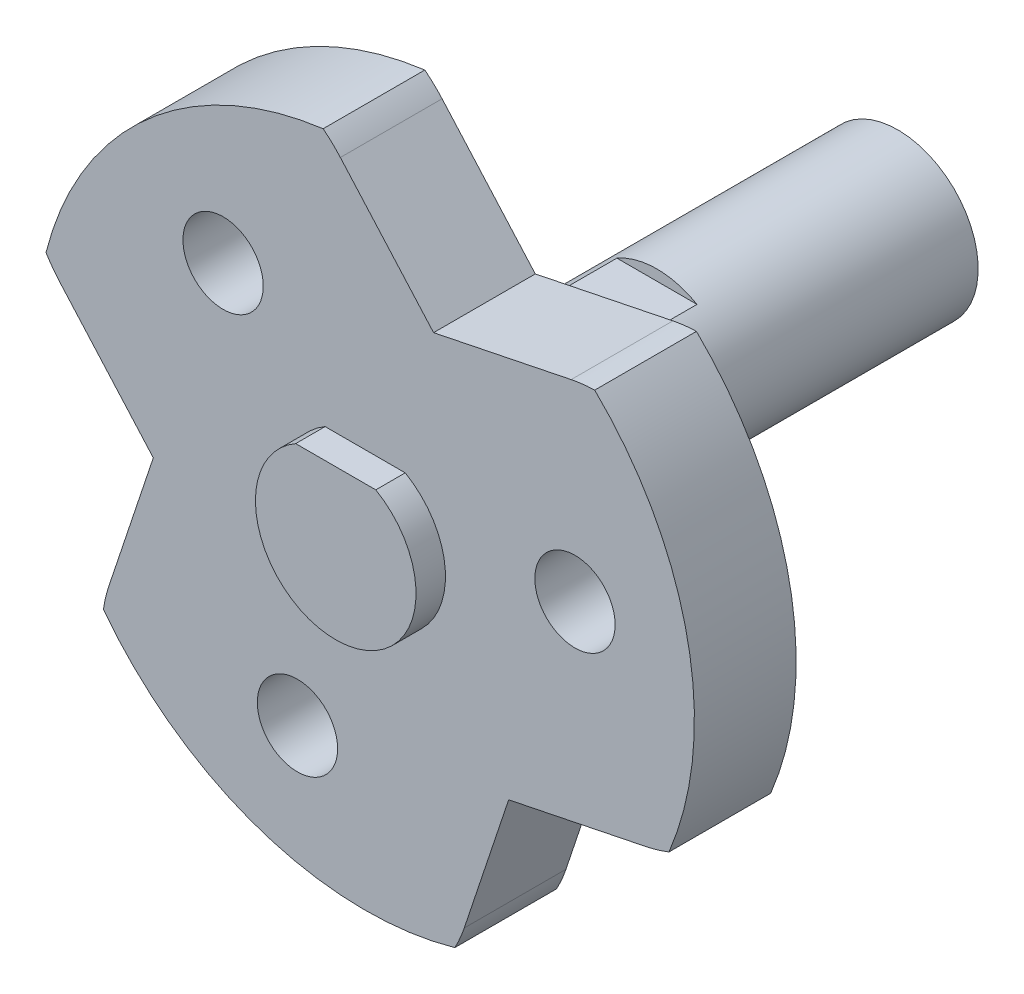
SolidWorks part; units mm, degrees
other "eje"
other "acople_prueba"
ref_plane "Alzado" through (0, 0, 0) normal (0, 0, 1) x (1, 0, 0)
ref_plane "Planta" through (0, 0, 0) normal (0, 1, 0) x (1, 0, 0)
ref_plane "Vista lateral" through (0, 0, 0) normal (1, 0, 0) x (0, 0, -1)
sketch "Croquis1" plane through (0, 0, 0) normal (0, 0, 1) x (1, 0, 0)
  line L0 (-3.993, 3) -> (5.9222, 3) construction
  line L1 (-1.4967, 2.6) -> (1.4967, 2.6)
  line L2 (-4.4025, -3) -> (5.8838, -3) construction
  arc A0 (-1.4967, 2.6) -> (1.4967, 2.6) centre (0, 0) ccw
  dimension "D1" = 6
  dimension "D2" = 5.6
extrude "Saliente-Extruir1" add sketch "Croquis1" along normal blind 12 contours A0 L1
sketch "Croquis2" plane through (0, 0, 0) normal (0, 0, -1) x (-1, 0, 0)
  circle A0 centre (0, 0) radius 3
extrude "Saliente-Extruir2" add sketch "Croquis2" along normal blind 9
sketch "Croquis3" plane through (0, 0, 12) normal (0, 0, 1) x (1, 0, 0)
  line L0 (-1.5492, 2.8) -> (1.5492, 2.8)
  line L1 (-1.4967, 2.6) -> (1.4967, 2.6) construction
  line L2 (-1.4967, 2.6) -> (1.4967, 2.6) construction
  line L4 (-4.4025, -3) -> (5.8838, -3) construction
  line L6 (-1.4967, 2.6) -> (1.4967, 2.6) construction
  arc A0 (-1.5492, 2.8) -> (1.5492, 2.8) centre (0, 0) ccw
  arc A1 (-1.4967, 2.6) -> (1.4967, 2.6) centre (0, 0) ccw construction
  circle A2 centre (0, 0) radius 5.7
  dimension "D1" = 0.2
  dimension "D3" = 2.5
  dimension "D2" = 0.2
  dimension "D4" = 5.6
extrude "Saliente-Extruir3" add sketch "Croquis3" against normal blind 8 separate body
sketch "Croquis4" plane through (0, 0, 4) normal (0, 0, -1) x (-1, 0, 0)
  circle A0 centre (0, 0) radius 3.2
  circle A1 centre (0, 0) radius 8.2
  arc A2 (-1.5492, 2.8) -> (1.5492, 2.8) centre (0, 0) ccw construction
extrude "Saliente-Extruir4" add sketch "Croquis4" along normal blind 5
sketch "Croquis5" plane through (0, 0, 4) normal (0, 0, 1) x (1, 0, 0)
  circle A0 centre (0, 0) radius 4.75
  circle A1 centre (0, 0) radius 8.2
  dimension "D1" = 9.5
extrude "Cortar-Extruir1" cut sketch "Croquis5" against normal through all and the other way through all
sketch "Croquis6" plane through (0, 0, -1) normal (0, 0, -1) x (-1, 0, 0)
  circle A0 centre (0, 0) radius 14.5
  circle A1 centre (0, 0) radius 4.75
  dimension "D1" = 29
extrude "Saliente-Extruir5" add sketch "Croquis6" against normal through all
sketch "Croquis7" plane through (0, 0, -1) normal (0, 0, -1) x (-1, 0, 0)
  circle A0 centre (0, 0) radius 8 construction
  circle A3 centre (-7.8376, 1.6038) radius 2.4
  circle A11 centre (5.3078, 5.9856) radius 2.4
  circle A12 centre (2.5298, -7.5895) radius 2.4
  point P11 (0, 0)
  point P17 (0, 0)
  dimension "D1" = 16
  dimension "D2" = 3
extrude "Cortar-Extruir2" cut sketch "Croquis7" against normal through all
sketch "Croquis8" plane through (0, 0, 12) normal (0, 0, 1) x (1, 0, 0)
  line L0 (-1.5492, 2.8) -> (1.5492, 2.8)
  line L1 (1.5492, 2.8) -> (1.806, 2.5219)
  circle A1 centre (-2.5298, -7.5895) radius 2.4
  circle A2 centre (0, 0) radius 8 construction
  circle A3 centre (0.0015, 0.0009) radius 8 construction
  circle A5 centre (0.0015, -0.0009) radius 8 construction
  circle A10 centre (7.8391, 1.603) radius 2.4 construction
  circle A11 centre (-5.3063, 5.9865) radius 2.4 construction
  circle A12 centre (-5.3078, 5.9856) radius 2.4
  circle A13 centre (7.8376, 1.6038) radius 2.4
  circle A14 centre (0.0015, 0.0009) radius 14.5017
  point P17 (0.001, 0)
  dimension "D1" = 3
extrude "Saliente-Extruir6" add sketch "Croquis8" along normal blind 3.8
sketch "Croquis9" plane through (0, 0, -1) normal (0, 0, -1) x (-1, 0, 0)
  circle A0 centre (0, 0) radius 14.5
extrude "Cortar-Extruir3" cut sketch "Croquis9" against normal blind 2.5
sketch "Croquis10" plane through (0, 0, 1.5) normal (0, 0, -1) x (-1, 0, 0)
  circle A0 centre (0, 0) radius 14.5
extrude "Cortar-Extruir4" cut sketch "Croquis10" against normal blind 5.6
sketch "Croquis11" plane through (0, 0, 15.8) normal (0, 0, 1) x (1, 0, 0)
  line L0 (-2.5298, -7.5895) -> (0, 0) construction
  line L1 (0, 0) -> (7.8376, 1.6038) construction
  line L2 (0, 0) -> (-5.3078, 5.9856) construction
  line L3 (0, 0) -> (9.6203, -10.8489) construction
  line L4 (0, 0) -> (4.5853, 13.7559) construction
  line L5 (0, 0) -> (-14.2056, -2.907) construction
  circle A0 centre (0, 0) radius 14.5 construction
  dimension "D1" = 120
  dimension "D2" = 60
  dimension "D3" = 60
  dimension "D4" = 60
sketch "Croquis12" plane through (0, 0, 15.8) normal (0, 0, 1) x (1, 0, 0)
  line L0 (0, 0) -> (-4.5853, -13.7559) construction
  line L1 (0, 0) -> (-9.6203, 10.8489) construction
  line L2 (0, 0) -> (14.2056, 2.907) construction
  line L3 (2.6219, -14.261) -> (5.3605, -6.0451)
  line L4 (5.3605, -6.0451) -> (13.845, -4.3089)
  line L5 (0, 0) -> (9.6203, -10.8489) construction
  line L6 (2.6219, -14.261) -> (13.845, -4.3089) construction
  line L7 (-13.6613, 4.8598) -> (-7.9155, -1.6198)
  line L8 (-7.9155, -1.6198) -> (-10.6541, -9.8356)
  line L9 (11.0394, 9.4011) -> (2.555, 7.6649)
  line L10 (2.555, 7.6649) -> (-3.1908, 14.1446)
  circle A0 centre (0, 0) radius 14.5
  circle A1 centre (0, 0) radius 14.5 construction
  circle A2 centre (-2.5298, -7.5895) radius 2.4 construction
  circle A3 centre (-5.3078, 5.9856) radius 2.4 construction
  circle A4 centre (7.8376, 1.6038) radius 2.4 construction
  circle A5 centre (0, 0) radius 14.5
  circle A6 centre (0, 0) radius 14.5
  point P32 (0, 0)
  circle M12 centre (0, 0) radius 14.5
  dimension "D1" = 120
  dimension "D2" = 120
  dimension "D3" = 120
  dimension "D4" = 60
  dimension "D5" = 120
  dimension "D6" = 15
  dimension "D7" = 3
extrude "Cortar-Extruir5" cut sketch "Croquis12" against normal up to next (8.7 mm away) contours L8 L7 M12 | L10 L9 M12 | L4 L3 M12
fillet "Redondeo2" radius 5 6 edges at (-13.6613, 4.8598, 11.45) (-3.1908, 14.1446, 11.45) (11.0394, 9.4011, 11.45) (13.845, -4.3089, 11.45) (2.6219, -14.261, 11.45) (-10.6541, -9.8356, 11.45)
ref_plane "Plano1" through (0, 0, 10.9) normal (0, 0, -1) x (-1, 0, 0)
sketch "Croquis13" plane through (0, 0, 15.8) normal (0, 0, 1) x (1, 0, 0)
  line L12 (-12.1456, 1.6433) -> (-9.0468, -1.8513)
  line L13 (-9.0468, -1.8513) -> (-10.5237, -6.2822)
  line L14 (4.6497, -11.34) -> (6.1266, -6.9091)
  line L15 (6.1266, -6.9091) -> (10.7024, -5.9727)
  line L16 (7.4959, 9.6967) -> (2.9201, 8.7604)
  line L17 (2.9201, 8.7604) -> (-0.1787, 12.2549)
  line L18 (-12.1456, 1.6433) -> (-9.0468, -1.8513)
  line L19 (-9.0468, -1.8513) -> (-10.5237, -6.2822)
  line L20 (4.6497, -11.34) -> (6.1266, -6.9091)
  line L21 (6.1266, -6.9091) -> (10.7024, -5.9727)
  line L22 (7.4959, 9.6967) -> (2.9201, 8.7604)
  line L23 (2.9201, 8.7604) -> (-0.1787, 12.2549)
  arc A18 (-7.616, 13.4999) -> (-12.4919, 9.1761) centre (0, 0) ccw
  arc A19 (-12.4919, 9.1761) -> (-12.1456, 1.6433) centre (-7.6563, 5.6241) ccw
  arc A20 (-10.5237, -6.2822) -> (-7.8832, -13.3456) centre (-4.8316, -8.1796) ccw
  arc A21 (-7.8832, -13.3456) -> (-1.7008, -15.4064) centre (0, 0) ccw
  arc A22 (-1.7008, -15.4064) -> (4.6497, -11.34) centre (-1.0424, -9.4426) ccw
  arc A23 (10.7024, -5.9727) -> (15.4992, -0.1543) centre (9.4995, -0.0945) ccw
  arc A24 (15.4992, -0.1543) -> (14.1927, 6.2303) centre (0, 0) ccw
  arc A25 (14.1927, 6.2303) -> (7.4959, 9.6967) centre (8.6988, 3.8186) ccw
  arc A26 (-0.1787, 12.2549) -> (-7.616, 13.4999) centre (-4.6679, 8.2741) ccw
  arc A27 (-7.616, 13.4999) -> (-12.4919, 9.1761) centre (0, 0) ccw
  arc A28 (-12.4919, 9.1761) -> (-12.1456, 1.6433) centre (-7.6563, 5.6241) ccw
  arc A29 (-10.5237, -6.2822) -> (-7.8832, -13.3456) centre (-4.8316, -8.1796) ccw
  arc A30 (-7.8832, -13.3456) -> (-1.7008, -15.4064) centre (0, 0) ccw
  arc A31 (-1.7008, -15.4064) -> (4.6497, -11.34) centre (-1.0424, -9.4426) ccw
  arc A32 (10.7024, -5.9727) -> (15.4992, -0.1543) centre (9.4995, -0.0945) ccw
  arc A33 (15.4992, -0.1543) -> (14.1927, 6.2303) centre (0, 0) ccw
  arc A34 (14.1927, 6.2303) -> (7.4959, 9.6967) centre (8.6988, 3.8186) ccw
  arc A35 (-0.1787, 12.2549) -> (-7.616, 13.4999) centre (-4.6679, 8.2741) ccw
  dimension "D1" = 1
extrude "Cortar-Extruir6" cut sketch "Croquis13" against normal up to surface (4.9 mm away) up to plane "Plano1"
sketch "Croquis14" plane through (0, 0, 10.9) normal (0, 0, 1) x (1, 0, 0)
  circle A2 centre (-2.5298, -7.5895) radius 2.4
  circle A3 centre (-2.5298, -7.5895) radius 2.4
  circle A5 centre (7.8376, 1.6038) radius 2.4
  circle A6 centre (7.8376, 1.6038) radius 2.4
  circle A7 centre (0, 0) radius 3.2
  circle A8 centre (-5.3078, 5.9856) radius 2.4
  circle A9 centre (-5.3078, 5.9856) radius 2.4
  circle A10 centre (0, 0) radius 2.25
  circle A11 centre (7.8376, 1.6038) radius 1.5
  circle A12 centre (-5.3078, 5.9856) radius 1.5
  circle A13 centre (-2.5298, -7.5895) radius 1.5
  point P17 (-5.1676, 5.9856)
  dimension "D4" = 4.5
  dimension "D5" = 3
  dimension "D6" = 3
  dimension "D1" = 0
  dimension "D2" = 0
  dimension "D3" = 0
extrude "Saliente-Extruir7" add sketch "Croquis14" against normal up to surface (3.8 mm away) up to face at (0, -0.2, 7.1)
sketch "Croquis15" plane through (0, 0, 10.9) normal (0, 0, 1) x (1, 0, 0)
  line L0 (-2.5298, -7.5895) -> (-3.8896, -11.6688) construction
  line L1 (0, 0) -> (-3.8896, -11.6688) construction
  circle A0 centre (0, 0) radius 12.3
  circle A1 centre (0, 0) radius 16.229
  dimension "D1" = 4.3
extrude "Cortar-Extruir7" cut sketch "Croquis15" against normal up to next (3.8 mm away) and the other way through all
